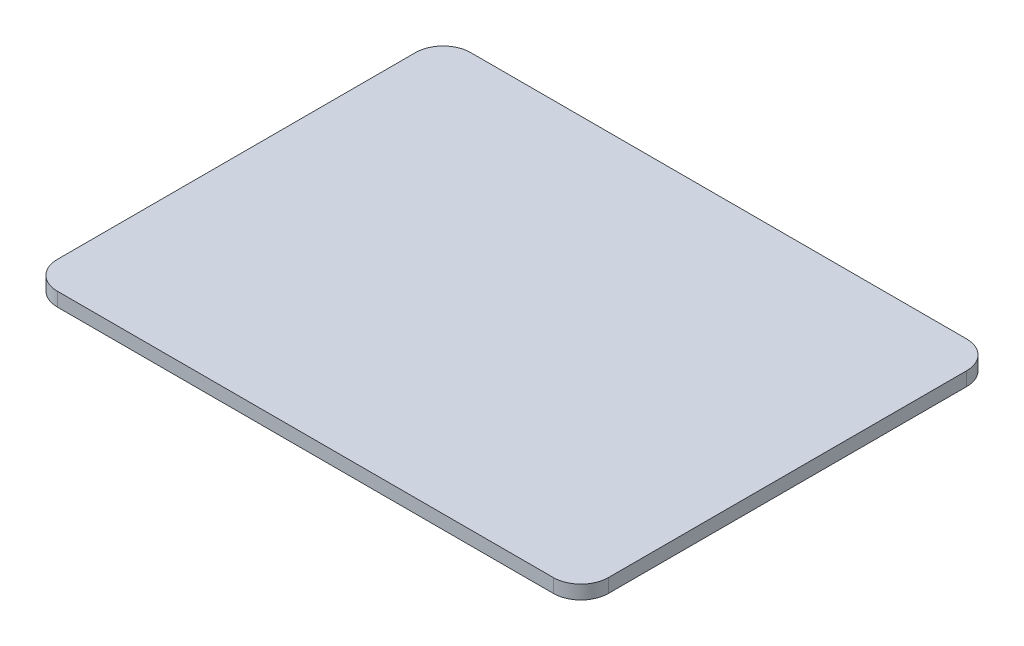
SolidWorks part; units mm, degrees
ref_plane "Front Plane" through (0, 0, 0) normal (0, 0, 1) x (1, 0, 0)
ref_plane "Top Plane" through (0, 0, 0) normal (0, 1, 0) x (1, 0, 0)
ref_plane "Right Plane" through (0, 0, 0) normal (1, 0, 0) x (0, 0, -1)
sketch "Sketch1" plane through (0, 0, 0) normal (0, 1, 0) x (1, 0, 0)
  line L1 (-4000, -3000) -> (4000, -3000)
  line L2 (-4000, -3000) -> (-4000, 3000)
  line L3 (-4000, 3000) -> (4000, 3000)
  line L4 (4000, -3000) -> (4000, 3000)
  line L5 (-4000, -3000) -> (4000, 3000) construction
  line L6 (-4000, 3000) -> (4000, -3000) construction
  point P0 (0, 0)
  dimension "D1" = 8000
  dimension "D2" = 6000
extrude "Boss-Extrude1" add sketch "Sketch1" along normal blind 200
fillet "Fillet1" radius 400 4 edges at (-4000, 100, -3000) (-4000, 100, 3000) (4000, 100, -3000) (4000, 100, 3000)
